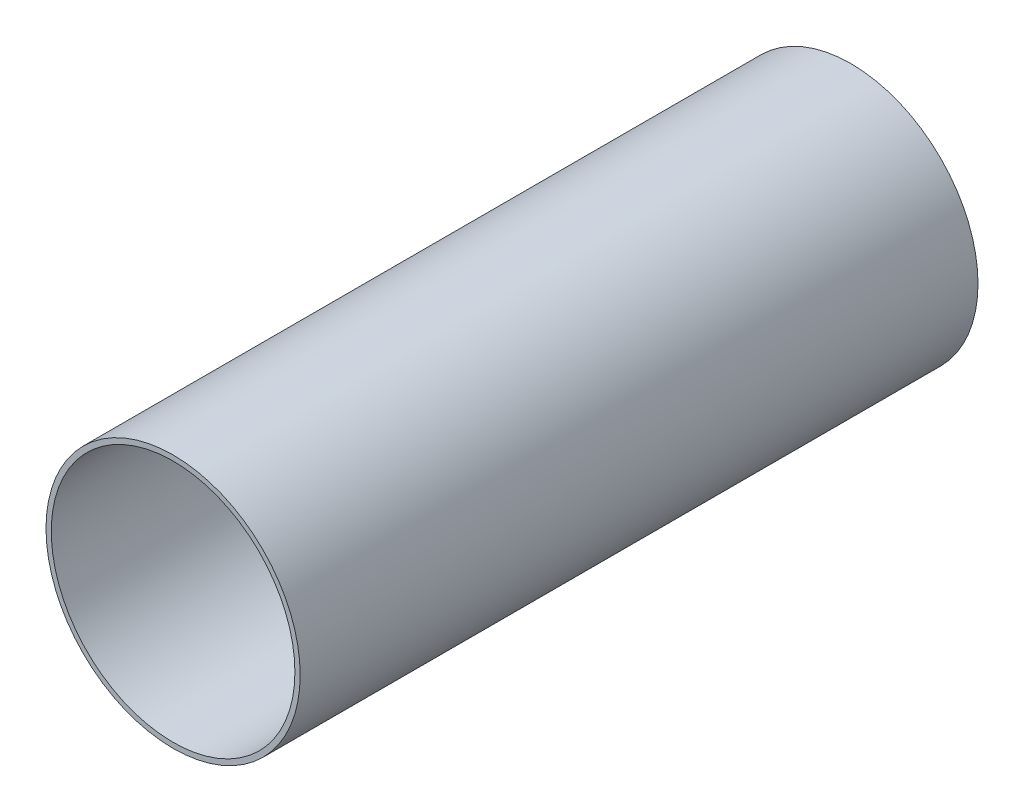
SolidWorks part; units mm, degrees
ref_plane "Front Plane" through (0, 0, 0) normal (0, 0, 1) x (1, 0, 0)
ref_plane "Top Plane" through (0, 0, 0) normal (0, 1, 0) x (1, 0, 0)
ref_plane "Right Plane" through (0, 0, 0) normal (1, 0, 0) x (0, 0, -1)
sketch "Sketch1" plane through (0, 0, 0) normal (0, 0, 1) x (1, 0, 0)
  circle A0 centre (0, 0) radius 38.1
  circle A1 centre (0, 0) radius 36.5252
  dimension "D1" = 76.2
  dimension "D2" = 73.0504
extrude "Boss-Extrude1" add sketch "Sketch1" along normal blind 203.2
